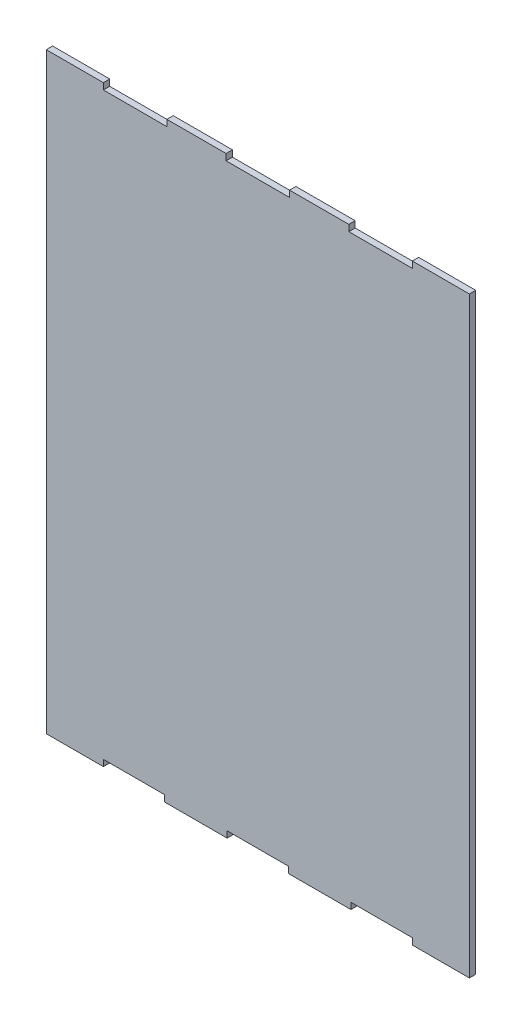
SolidWorks part; units mm, degrees
ref_plane "前基準面" through (0, 0, 0) normal (0, 0, 1) x (1, 0, 0)
ref_plane "上基準面" through (0, 0, 0) normal (0, 1, 0) x (1, 0, 0)
ref_plane "右基準面" through (0, 0, 0) normal (1, 0, 0) x (0, 0, -1)
sketch "草圖1" plane through (0, 0, 0) normal (0, 0, 1) x (1, 0, 0)
  line L0 (-11.5, -140) -> (-11.5, -137)
  line L1 (-97, 140) -> (-70, 140)
  line L2 (-97, 140) -> (-97, -140)
  line L3 (-97, -140) -> (-70, -140)
  line L4 (103, 140) -> (103, -140)
  line L5 (-41, -140) -> (-11.5, -140)
  line L6 (17.5, -140) -> (47, -140)
  line L8 (-70, -140) -> (-70, -137)
  line L9 (-70, -137) -> (-41, -137)
  line L10 (-41, -140) -> (-41, -137)
  line L12 (17.5, -140) -> (17.5, -137)
  line L13 (-11.5, -137) -> (17.5, -137)
  line L14 (47, -140) -> (47, -137)
  line L16 (76, -140) -> (76, -137)
  line L17 (47, -137) -> (76, -137)
  line L18 (-12, 140) -> (-12, 137)
  line L20 (-70, 140) -> (-70, 137)
  line L21 (-70, 137) -> (-40, 137)
  line L22 (-40, 140) -> (-40, 137)
  line L24 (18, 140) -> (18, 137)
  line L25 (-12, 137) -> (18, 137)
  line L26 (46, 140) -> (46, 137)
  line L28 (76, 140) -> (76, 137)
  line L29 (46, 137) -> (76, 137)
  line L30 (-41, -140) -> (-11.5, -140)
  line L31 (17.5, -140) -> (47, -140)
  line L32 (76, -140) -> (103, -140)
  line L33 (-40, 140) -> (-12, 140)
  line L34 (18, 140) -> (46, 140)
  line L35 (76, 140) -> (103, 140)
  line L36 (76, -140) -> (103, -140)
  line L37 (-97, 140) -> (-70, 140)
  line L38 (-97, 140) -> (-97, -140)
  line L39 (-97, -140) -> (-70, -140)
  line L40 (103, 140) -> (103, -140)
  line L41 (-40, 140) -> (-12, 140)
  line L42 (18, 140) -> (46, 140)
  line L43 (76, 140) -> (103, 140)
  point P0 (0, 0)
  dimension "D1" = 200
  dimension "D2" = 280
  dimension "D3" = 27
  dimension "D4" = 29
  dimension "D5" = 3
  dimension "D7" = 27
  dimension "D8" = 30
  dimension "D9" = 27
  dimension "D10" = 3
  dimension "D12" = 27
  dimension "D6" = 3
  dimension "D11" = 3
extrude "填料-伸長1" add sketch "草圖1" along normal blind 3 contours L35 L28 L29 L26 L34 L24 L25 L18 L33 L22 L21 L20 L1 L2 L3 L8 L9 L10 L5 L0 L13 L12 L6 L14 L17 L16 L32 L4
